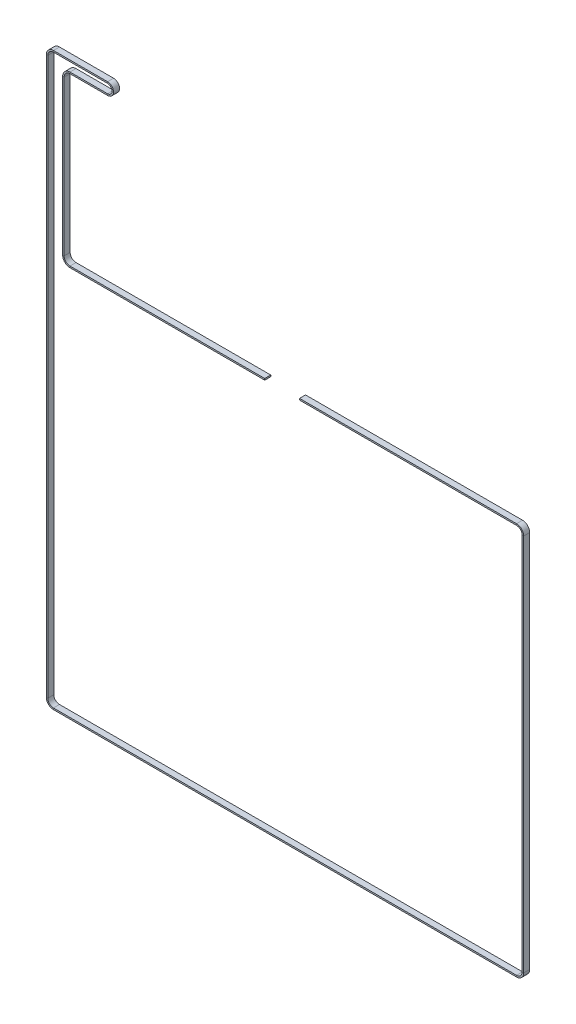
SolidWorks part; units mm, degrees
ref_plane "Front" through (0, 0, 0) normal (0, 0, 1) x (1, 0, 0)
ref_plane "Top" through (0, 0, 0) normal (0, 1, 0) x (1, 0, 0)
ref_plane "Right" through (0, 0, 0) normal (1, 0, 0) x (0, 0, -1)
sketch "Sketch1" plane through (0, -21, 4.45) normal (0, 0, 1) x (1, 0, 0)
  line L0 (10, 63.3) -> (47.5, 63.3)
  line L1 (47.5, 73.7) -> (-6.5, 73.7)
  line L2 (-12.875, 67.325) -> (-12.875, -488)
  line L3 (-6.5, -494.375) -> (455.5, -494.375)
  line L4 (461.875, -488) -> (461.875, -110.5436)
  line L5 (455.5, -104.1686) -> (239.0011, -104.1686)
  line L7 (3.4, 56.7) -> (3.4, -97.7186)
  line L8 (10, -104.3186) -> (204.3011, -104.3186)
  line L10 (204.3011, -104.2186) -> (204.3011, -107.7186) construction
  line L11 (239.0011, -103.3186) -> (239.0011, -96.7186) construction
  circle A0 centre (47.5, 68.5) radius 5.2 construction
  circle A1 centre (10, 56.7) radius 6.6 construction
  circle A2 centre (-6.5, 67.325) radius 6.375 construction
  circle A4 centre (-6.5, -488) radius 6.375 construction
  circle A5 centre (455.5, -488) radius 6.375 construction
  arc A7 (47.5, 73.7) -> (47.5, 63.3) centre (47.5, 68.5) cw
  arc A8 (10, 63.3) -> (3.4, 56.7) centre (10, 56.7) ccw
  arc A9 (-12.875, 67.325) -> (-6.5, 73.7) centre (-6.5, 67.325) cw
  arc A10 (-6.5, -494.375) -> (-12.875, -488) centre (-6.5, -488) cw
  arc A11 (455.5, -494.375) -> (461.875, -488) centre (455.5, -488) ccw
  arc A12 (461.875, -110.5436) -> (455.5, -104.1686) centre (455.5, -110.5436) ccw
  arc A13 (3.4, -97.7186) -> (10, -104.3186) centre (10, -97.7186) ccw
  circle A14 centre (-6.5, 67.325) radius 9 construction
  circle A15 centre (10, -97.7186) radius 6.6 construction
  circle A16 centre (10, -97.7186) radius 5.9875 construction
  circle A17 centre (455.5, -110.5436) radius 6.375 construction
  circle A18 centre (455.5, -110.5436) radius 5.9875 construction
  dimension "D1" = 12.75
ref_plane "Plane1" through (239.0011, -125.1686, 4.45) normal (-1, 0, 0) x (0, 0, 1)
sketch "Sketch2" plane through (239.0011, -125.1686, 4.45) normal (-1, 0, 0) x (0, 0, 1)
  line L1 (-3, 0.75) -> (3, 0.75)
  line L2 (-3, 0.75) -> (-3, -0.75)
  line L3 (-3, -0.75) -> (3, -0.75)
  line L4 (3, 0.75) -> (3, -0.75)
  line L5 (-3, 0.75) -> (3, -0.75) construction
  line L6 (-3, -0.75) -> (3, 0.75) construction
  point P0 (0, 0)
  dimension "D1" = 6
  dimension "D2" = 1.5
sweep "Sweep1" add profiles "Sketch2" path "Sketch1"
